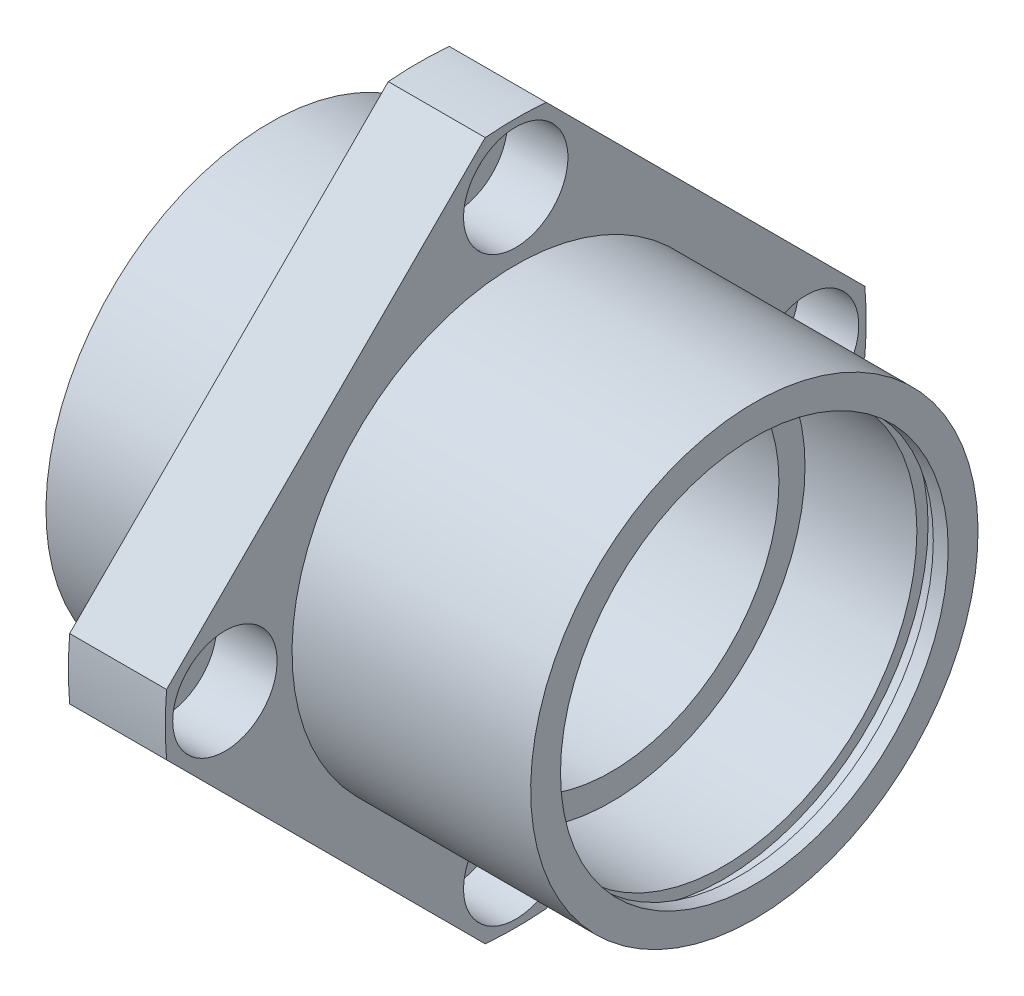
SolidWorks part; units mm, degrees
ref_plane "Plano frontal" through (0, 0, 0) normal (0, 0, 1) x (1, 0, 0)
ref_plane "Plano superior" through (0, 0, 0) normal (0, 1, 0) x (1, 0, 0)
ref_plane "Plano direito" through (0, 0, 0) normal (1, 0, 0) x (0, 0, -1)
ref_plane "Plane1" through (0, 0, 0) normal (0, 0, 1) x (1, 0, 0)
sketch "Sketch1" plane through (0, 0, 0) normal (0, 0, 1) x (1, 0, 0)
  line L0 (-65, 0) -> (-65, 30)
  line L1 (-65, 30) -> (-45, 30)
  line L2 (-45, 30) -> (-45, 47)
  line L3 (-45, 47) -> (-32, 47)
  line L4 (-32, 47) -> (-32, 30)
  line L5 (-32, 30) -> (0, 30)
  line L6 (0, 30) -> (0, 0)
  line L7 (0, 0) -> (-65, 0)
  line L8 (0, 0) -> (-65, 0) construction
revolve "Revolve1" add sketch "Sketch1" angle 360 about L8
ref_plane "Plane2" through (0, 0, 0) normal (0, 0, 1) x (1, 0, 0)
sketch "Sketch2" plane through (0, 0, 0) normal (0, 0, 1) x (1, 0, 0)
  line L0 (-65, 0) -> (-65, 26)
  line L1 (-65, 26) -> (-63, 26)
  line L2 (-63, 26) -> (-63, 27.5)
  line L3 (-63, 27.5) -> (-60.8, 27.5)
  line L4 (-60.8, 27.5) -> (-60.8, 26)
  line L5 (-60.8, 26) -> (-45.8, 26)
  line L6 (-45.8, 26) -> (-45.8, 22.5)
  line L7 (-45.8, 22.5) -> (-19.2, 22.5)
  line L8 (-19.2, 22.5) -> (-19.2, 26)
  line L9 (-19.2, 26) -> (-4.2, 26)
  line L10 (-4.2, 26) -> (-4.2, 27.5)
  line L11 (-4.2, 27.5) -> (-2, 27.5)
  line L12 (-2, 27.5) -> (-2, 26)
  line L13 (-2, 26) -> (0, 26)
  line L14 (0, 26) -> (0, 0)
  line L15 (0, 0) -> (-65, 0)
  line L16 (0, 0) -> (-65, 0) construction
revolve "Cut-Revolve1" cut sketch "Sketch2" angle 360 about L16
ref_plane "Plane3" through (0, 0, 0) normal (0, 0, 1) x (1, 0, 0)
sketch "Sketch3" plane through (0, 0, 0) normal (0, 0, 1) x (1, 0, 0)
  line L0 (-45, 39) -> (-45, 43.5)
  line L1 (-45, 43.5) -> (-40.1, 43.5)
  line L2 (-40.1, 43.5) -> (-40.1, 46)
  line L3 (-40.1, 46) -> (-32, 46)
  line L4 (-32, 46) -> (-32, 39)
  line L5 (-32, 39) -> (-45, 39)
  line L6 (-32, 39) -> (-45, 39) construction
revolve "Cut-Revolve2" cut sketch "Sketch3" angle 360 about L6
ref_plane "Plane4" through (0, 0, 39) normal (0, 0, 1) x (1, 0, 0)
sketch "Sketch4" plane through (0, 0, 39) normal (0, 0, 1) x (1, 0, 0)
  line L0 (-45, 0) -> (-45, 4.5)
  line L1 (-45, 4.5) -> (-40.1, 4.5)
  line L2 (-40.1, 4.5) -> (-40.1, 7)
  line L3 (-40.1, 7) -> (-32, 7)
  line L4 (-32, 7) -> (-32, 0)
  line L5 (-32, 0) -> (-45, 0)
  line L6 (-32, 0) -> (-45, 0) construction
revolve "Cut-Revolve3" cut sketch "Sketch4" angle 360 about L6
ref_plane "Plane5" through (0, 0, 0) normal (0, 0, 1) x (1, 0, 0)
sketch "Sketch5" plane through (0, 0, 0) normal (0, 0, 1) x (1, 0, 0)
  line L0 (-45, -39) -> (-45, -34.5)
  line L1 (-45, -34.5) -> (-40.1, -34.5)
  line L2 (-40.1, -34.5) -> (-40.1, -32)
  line L3 (-40.1, -32) -> (-32, -32)
  line L4 (-32, -32) -> (-32, -39)
  line L5 (-32, -39) -> (-45, -39)
  line L6 (-32, -39) -> (-45, -39) construction
revolve "Cut-Revolve4" cut sketch "Sketch5" angle 360 about L6
ref_plane "Plane6" through (0, 0, -39) normal (0, 0, 1) x (1, 0, 0)
sketch "Sketch6" plane through (0, 0, -39) normal (0, 0, 1) x (1, 0, 0)
  line L0 (-45, 0) -> (-45, 4.5)
  line L1 (-45, 4.5) -> (-40.1, 4.5)
  line L2 (-40.1, 4.5) -> (-40.1, 7)
  line L3 (-40.1, 7) -> (-32, 7)
  line L4 (-32, 7) -> (-32, 0)
  line L5 (-32, 0) -> (-45, 0)
  line L6 (-32, 0) -> (-45, 0) construction
revolve "Cut-Revolve5" cut sketch "Sketch6" angle 360 about L6
ref_plane "Plane7" through (-32, 0, 0) normal (1, 0, 0) x (0, 0, -1)
sketch "Sketch7" plane through (-32, 0, 0) normal (1, 0, 0) x (0, 0, -1)
  line L0 (-50.9117, 0) -> (0, -50.9117)
  line L1 (0, -50.9117) -> (50.9117, 0)
  line L2 (50.9117, 0) -> (0, 50.9117)
  line L3 (0, 50.9117) -> (-50.9117, 0)
  circle A0 centre (0, 0) radius 72
extrude "Cut-Extrude1" cut sketch "Sketch7" against normal blind 13
